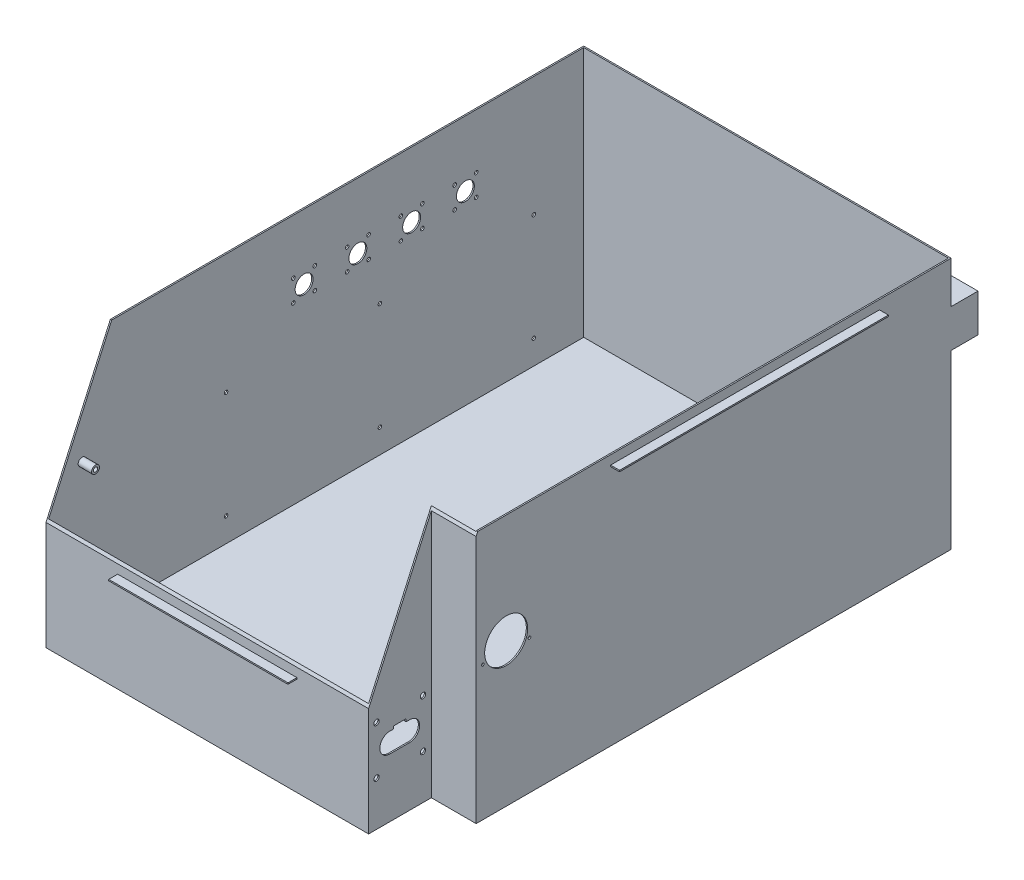
SolidWorks part; units mm, degrees
ref_plane "Front Plane" through (0, 0, 0) normal (0, 0, 1) x (1, 0, 0)
ref_plane "Top Plane" through (0, 0, 0) normal (0, 1, 0) x (1, 0, 0)
ref_plane "Right Plane" through (0, 0, 0) normal (1, 0, 0) x (0, 0, -1)
sketch "Sketch1" plane through (0, 0, 0) normal (0, 1, 0) x (1, 0, 0)
  line L1 (-205, 300) -> (205, 300)
  line L2 (-205, 300) -> (-205, -300)
  line L3 (-205, -300) -> (155, -300)
  line L4 (205, 300) -> (205, -230)
  line L6 (205, -230) -> (155, -230)
  line L7 (155, -230) -> (155, -300)
  line L8 (0, -330) -> (0, 330) construction
  point P1 (0, 300)
  point P12 (-205, -6.3782)
  dimension "D1" = 600
  dimension "D2" = 410
  dimension "D3" = 300
  dimension "D5" = 70
  dimension "D6" = 50
extrude "Boss-Extrude1" add sketch "Sketch1" along normal blind 1.5
sketch "Sketch2" plane through (0, 1.5, 0) normal (0, 1, 0) x (1, 0, 0)
  line L60 (-203.5, 298.5) -> (-203.5, -298.5)
  line L61 (-203.5, -298.5) -> (153.5, -298.5)
  line L62 (153.5, -298.5) -> (153.5, -228.5)
  line L63 (153.5, -228.5) -> (203.5, -228.5)
  line L64 (203.5, -228.5) -> (203.5, 298.5)
  line L65 (203.5, 298.5) -> (-203.5, 298.5)
  line L66 (-205, 300) -> (-205, -300)
  line L67 (-205, -300) -> (155, -300)
  line L68 (155, -300) -> (155, -230)
  line L69 (155, -230) -> (205, -230)
  line L70 (205, -230) -> (205, 300)
  line L71 (205, 300) -> (-205, 300)
  line L72 (-205, 300) -> (-205, -300)
  line L73 (-205, -300) -> (155, -300)
  line L74 (155, -300) -> (155, -230)
  line L75 (155, -230) -> (205, -230)
  line L76 (205, -230) -> (205, 300)
  line L77 (205, 300) -> (-205, 300)
  dimension "D1" = 0
  dimension "D2" = 1.5
extrude "Boss-Extrude2" add sketch "Sketch2" along normal blind 280
sketch "Sketch3" plane through (-205, 0, 0) normal (-1, 0, 0) x (0, 0, 1)
  line L3 (300, 281.5) -> (300, 0) construction
  line L4 (300, 121.1176) -> (228.1952, 281.5)
  line L6 (-300, 281.5) -> (300, 281.5) construction
  line L9 (300, 281.5) -> (300, 121.1176)
  line L10 (228.1952, 281.5) -> (300, 281.5)
sketch "Sketch4" plane through (0, 0, -300) normal (0, 0, -1) x (-1, 0, 0)
  line L0 (-205, 281.5) -> (-205, 0) construction
  line L1 (-205, 234.6761) -> (205, 234.6761)
  line L2 (-205, 234.6761) -> (-205, 192.2905)
  line L3 (-205, 192.2905) -> (205, 192.2905)
  line L4 (205, 234.6761) -> (205, 192.2905)
  line L5 (205, 281.5) -> (205, 0) construction
extrude "Boss-Extrude3" add sketch "Sketch4" along normal blind 30
extrude "Cut-Extrude1" cut sketch "Sketch3" against normal through all both and the other way through all
sketch "Sketch5" plane through (-205, 0, 0) normal (-1, 0, 0) x (0, 0, 1)
  line L0 (-178.5, 196.6666) -> (-178.5, 220.6666) construction
  line L5 (-178.5, 196.6666) -> (-154.5, 196.6666) construction
  line L6 (-178.5, 220.6666) -> (-154.5, 220.6666) construction
  line L7 (-154.5, 196.6666) -> (-154.5, 220.6666) construction
  line L8 (-178.5, 196.6666) -> (-154.5, 220.6666) construction
  line L9 (-178.5, 220.6666) -> (-154.5, 196.6666) construction
  line L10 (-118.5, 196.6666) -> (-118.5, 220.6666) construction
  line L11 (-118.5, 196.6666) -> (-94.5, 196.6666) construction
  line L14 (-118.5, 220.6666) -> (-94.5, 220.6666) construction
  line L16 (-94.5, 196.6666) -> (-94.5, 220.6666) construction
  line L17 (-118.5, 196.6666) -> (-94.5, 220.6666) construction
  line L20 (-118.5, 220.6666) -> (-94.5, 196.6666) construction
  line L22 (-58.5, 196.6666) -> (-58.5, 220.6666) construction
  line L23 (-58.5, 196.6666) -> (-34.5, 196.6666) construction
  line L26 (-58.5, 220.6666) -> (-34.5, 220.6666) construction
  line L28 (-298.5, 281.5) -> (-298.5, 1.5) construction
  line L29 (-34.5, 196.6666) -> (-34.5, 220.6666) construction
  line L30 (-58.5, 196.6666) -> (-34.5, 220.6666) construction
  line L31 (-58.5, 220.6666) -> (-34.5, 196.6666) construction
  line L32 (1.5, 196.6666) -> (1.5, 220.6666) construction
  line L33 (1.5, 196.6666) -> (25.5, 196.6666) construction
  line L34 (1.5, 220.6666) -> (25.5, 220.6666) construction
  line L35 (25.5, 196.6666) -> (25.5, 220.6666) construction
  line L36 (1.5, 196.6666) -> (25.5, 220.6666) construction
  line L37 (1.5, 220.6666) -> (25.5, 196.6666) construction
  circle A0 centre (-178.5, 220.6666) radius 2
  circle A2 centre (-154.5, 196.6666) radius 2
  circle A3 centre (-154.5, 220.6666) radius 2
  circle A4 centre (-166.5, 208.6666) radius 10
  circle A20 centre (-178.5, 196.6666) radius 2
  circle A21 centre (-118.5, 220.6666) radius 2
  circle A22 centre (-94.5, 196.6666) radius 2
  circle A23 centre (-94.5, 220.6666) radius 2
  circle A24 centre (-106.5, 208.6666) radius 10
  circle A25 centre (-118.5, 196.6666) radius 2
  circle A26 centre (-58.5, 220.6666) radius 2
  circle A27 centre (-34.5, 196.6666) radius 2
  circle A28 centre (-34.5, 220.6666) radius 2
  circle A29 centre (-46.5, 208.6666) radius 10
  circle A30 centre (-58.5, 196.6666) radius 2
  circle A31 centre (1.5, 220.6666) radius 2
  circle A32 centre (25.5, 196.6666) radius 2
  circle A33 centre (25.5, 220.6666) radius 2
  circle A34 centre (13.5, 208.6666) radius 10
  circle A35 centre (1.5, 196.6666) radius 2
  point P9 (-166.5, 208.6666)
  point P23 (-106.5, 208.6666)
  point P36 (-46.5, 208.6666)
  point P49 (13.5, 208.6666)
  dimension "D2" = 20
  dimension "D5" = 4
  dimension "D1" = 4
  dimension "D8" = 4
  dimension "D3" = 24
  dimension "D4" = 24
  dimension "D7" = 120
  dimension "D6" = 4
sketch "Sketch6" plane through (-203.5, 0, 0) normal (1, 0, 0) x (0, 0, -1)
  arc A0 (151.1392, 167.4539) -> (156.7272, 167.4539) centre (153.9332, 167.4539) ccw construction
  arc A1 (-68.8756, 167.4539) -> (-63.2876, 167.4539) centre (-66.0816, 167.4539) ccw construction
  arc A2 (-178.883, 167.4539) -> (-173.295, 167.4539) centre (-176.089, 167.4539) ccw construction
  arc A3 (151.1392, 167.4539) -> (156.7272, 167.4539) centre (153.9332, 167.4539) ccw
  arc A4 (-68.8756, 167.4539) -> (-63.2876, 167.4539) centre (-66.0816, 167.4539) ccw
  arc A5 (-178.883, 167.4539) -> (-173.295, 167.4539) centre (-176.089, 167.4539) ccw
  circle A6 centre (-176.089, 167.4539) radius 2.794
  circle A7 centre (-176.089, 167.4539) radius 4.5
  circle A8 centre (-64.4633, 167.4539) radius 4.5
  circle A9 centre (-64.4633, 167.4539) radius 2.794
  circle A10 centre (155.5515, 167.4539) radius 2.794
  circle A11 centre (155.5515, 167.4539) radius 4.5
  dimension "D1" = 9
extrude "Boss-Extrude4" [suppressed] add sketch "Sketch6" along normal blind 50 contours A4 A9 | A8 | A7 | A6 | A11 | A10
sketch "Sketch8" plane through (-203.5, 0, 0) normal (1, 0, 0) x (0, 0, -1)
  line L0 (298.5, 1.5) -> (-298.5, 1.5) construction
  line L1 (-298.5, 124.4679) -> (-298.5, 1.5) construction
  circle A0 centre (-261.2404, 161.0978) radius 2.39
  circle A1 centre (-261.2404, 161.0978) radius 4.39
  circle A2 centre (-203.5, 16.5) radius 2.39
  circle A3 centre (-203.5, 16.5) radius 4.39
  dimension "D3" = 4.78
  dimension "D4" = 2
  dimension "D1" = 155.7
  dimension "D2" = 15
  dimension "D5" = 95
extrude "Boss-Extrude5" add sketch "Sketch8" along normal blind 15
sketch "Sketch10" plane through (153.5, 0, 0) normal (-1, 0, 0) x (0, 0, 1)
  line L0 (254, 86.5) -> (259.25, 86.5) construction
  line L1 (254, 66.5) -> (276.5, 66.5) construction
  line L2 (276.5, 76.5) -> (254, 76.5) construction
  line L3 (298.5, 1.5) -> (228.5, 1.5) construction
  line L5 (259.25, 86.5) -> (259.25, 89.5) construction
  line L6 (259.25, 89.5) -> (271.25, 89.5) construction
  line L7 (271.25, 86.5) -> (271.25, 89.5) construction
  line L8 (298.5, 124.4679) -> (298.5, 1.5) construction
  line L9 (271.25, 86.5) -> (276.5, 86.5) construction
  line L10 (258.25, 90.5) -> (272.25, 90.5)
  line L11 (272.25, 87.5) -> (272.25, 90.5)
  line L12 (272.25, 87.5) -> (276.5, 87.5)
  line L13 (254, 65.5) -> (276.5, 65.5)
  line L14 (254, 87.5) -> (258.25, 87.5)
  line L15 (258.25, 87.5) -> (258.25, 90.5)
  line L17 (239.3, 49.55) -> (291.2, 49.55) construction
  line L18 (239.3, 49.55) -> (239.3, 103.45) construction
  line L19 (239.3, 103.45) -> (291.2, 103.45) construction
  line L20 (291.2, 49.55) -> (291.2, 103.45) construction
  line L21 (239.3, 49.55) -> (291.2, 103.45) construction
  line L22 (239.3, 103.45) -> (291.2, 49.55) construction
  arc A0 (254, 86.5) -> (254, 66.5) centre (254, 76.5) ccw construction
  arc A1 (276.5, 66.5) -> (276.5, 86.5) centre (276.5, 76.5) ccw construction
  arc A2 (276.5, 65.5) -> (276.5, 87.5) centre (276.5, 76.5) ccw
  arc A3 (254, 87.5) -> (254, 65.5) centre (254, 76.5) ccw
  circle A4 centre (239.3, 103.45) radius 3
  circle A5 centre (291.2, 103.45) radius 3
  circle A6 centre (239.3, 49.55) radius 3
  circle A7 centre (291.2, 49.55) radius 3
  point P12 (265.25, 89.5)
  point P13 (265.25, 76.5)
  point P26 (265.25, 76.5)
  dimension "D1" = 65
  dimension "D2" = 22.5
  dimension "D6" = 20
  dimension "D10" = 6
  dimension "D3" = 22
  dimension "D4" = 12
  dimension "D5" = 3
  dimension "D8" = 51.9
  dimension "D9" = 53.9
  dimension "D7" = 1
extrude "Cut-Extrude2" cut sketch "Sketch10" against normal up to surface (1.5 mm away)
sketch "Sketch11" plane through (153.5, 0, 0) normal (-1, 0, 0) x (0, 0, 1)
  line L0 (298.4737, 103.43) -> (298.4737, 49.53) construction
  line L13 (254, 66.5) -> (276.5, 66.5) construction
  line L14 (254, 86.5) -> (259.25, 86.5) construction
  line L15 (254, 66.5) -> (276.5, 66.5)
  line L19 (254, 86.5) -> (318.4237, 86.5)
  line L20 (272.25, 90.5) -> (258.25, 90.5)
  line L21 (272.25, 90.5) -> (258.25, 90.5)
  line L22 (272.25, 87.5) -> (272.25, 90.5)
  line L23 (272.25, 87.5) -> (272.25, 90.5)
  line L28 (330.4237, 86.5) -> (259.25, 86.5)
  line L29 (254.1078, 66) -> (276.5284, 66)
  line L30 (330.9237, 86) -> (258.6115, 86)
  line L31 (330.9237, 86) -> (330.9237, 91)
  line L32 (330.9237, 91) -> (317.9237, 91)
  line L33 (317.9237, 91) -> (317.9237, 87)
  line L34 (254.1078, 87) -> (317.9237, 87)
  line L36 (298.4737, 103.43) -> (350.3737, 103.43) construction
  line L43 (272.25, 90.5) -> (258.25, 90.5)
  line L44 (272.25, 90.5) -> (258.25, 90.5)
  line L45 (272.25, 87.5) -> (272.25, 90.5)
  line L46 (272.25, 87.5) -> (272.25, 90.5)
  line L47 (276.5, 87.5) -> (272.25, 87.5)
  line L48 (276.5, 87.5) -> (272.25, 87.5)
  line L49 (254, 65.5) -> (276.5, 65.5)
  line L50 (254, 65.5) -> (276.5, 65.5)
  line L51 (258.25, 87.5) -> (254, 87.5)
  line L52 (258.25, 87.5) -> (254, 87.5)
  line L53 (258.25, 90.5) -> (258.25, 87.5)
  line L54 (258.25, 90.5) -> (258.25, 87.5)
  line L55 (272.25, 90.5) -> (258.25, 90.5)
  line L56 (272.25, 90.5) -> (258.25, 90.5)
  line L57 (272.25, 87.5) -> (272.25, 90.5)
  line L58 (272.25, 87.5) -> (272.25, 90.5)
  line L59 (276.5, 87.5) -> (272.25, 87.5)
  line L60 (276.5, 87.5) -> (272.25, 87.5)
  line L61 (254, 65.5) -> (276.5, 65.5)
  line L62 (254, 65.5) -> (276.5, 65.5)
  line L63 (258.25, 87.5) -> (254, 87.5)
  line L64 (258.25, 87.5) -> (254, 87.5)
  line L65 (258.25, 90.5) -> (258.25, 87.5)
  line L66 (258.25, 90.5) -> (258.25, 87.5)
  line L67 (330.4237, 86.5) -> (330.4237, 90.5) construction
  line L68 (330.4237, 90.5) -> (318.4237, 90.5) construction
  line L69 (318.4237, 90.5) -> (318.4237, 86.5) construction
  line L70 (276.5, 87.5) -> (272.25, 87.5)
  line L71 (276.5, 87.5) -> (272.25, 87.5)
  line L72 (254, 65.5) -> (276.5, 65.5)
  line L73 (254, 65.5) -> (276.5, 65.5)
  line L74 (258.25, 87.5) -> (254, 87.5)
  line L75 (258.25, 87.5) -> (254, 87.5)
  line L76 (258.25, 90.5) -> (258.25, 87.5)
  line L77 (258.25, 90.5) -> (258.25, 87.5)
  arc A4 (276.5284, 66) -> (258.6115, 86) centre (274.6748, 82.3648) ccw
  arc A5 (276.5, 65.5) -> (276.5, 87.5) centre (276.5, 76.5) ccw
  arc A7 (276.5, 65.5) -> (276.5, 87.5) centre (276.5, 76.5) ccw
  arc A9 (254.1078, 87) -> (254.1078, 66) centre (249.4174, 76.5) ccw
  circle A10 centre (298.4737, 103.43) radius 3
  circle A11 centre (298.4737, 49.53) radius 3
  circle A12 centre (350.3737, 103.43) radius 3
  circle A13 centre (350.3737, 49.53) radius 3
  arc A16 (276.5, 66.5) -> (259.25, 86.5) centre (274.6748, 82.3648) ccw construction
  arc A17 (276.5, 65.5) -> (276.5, 87.5) centre (276.5, 76.5) ccw
  arc A18 (254, 87.5) -> (254, 65.5) centre (254, 76.5) ccw
  arc A19 (254, 87.5) -> (254, 65.5) centre (254, 76.5) ccw
  arc A20 (254, 86.5) -> (254, 66.5) centre (249.4174, 76.5) ccw construction
  arc A21 (276.5, 65.5) -> (276.5, 87.5) centre (276.5, 76.5) ccw
  arc A22 (254, 87.5) -> (254, 65.5) centre (254, 76.5) ccw
  arc A23 (254, 87.5) -> (254, 65.5) centre (254, 76.5) ccw
  arc A24 (276.5, 65.5) -> (276.5, 87.5) centre (276.5, 76.5) ccw
  arc A25 (276.5, 65.5) -> (276.5, 87.5) centre (276.5, 76.5) ccw
  arc A26 (254, 87.5) -> (254, 65.5) centre (254, 76.5) ccw
  arc A27 (254, 87.5) -> (254, 65.5) centre (254, 76.5) ccw
  dimension "D5" = 6
  dimension "D6" = 51.9
  dimension "D7" = 53.9
  dimension "D1" = 0
  dimension "D2" = 0
  dimension "D3" = 0
  dimension "D4" = 0.5
extrude "Cut-Extrude3" [suppressed] cut sketch "Sketch11" against normal through all
sketch "Sketch14" plane through (153.5, 0, 0) normal (-1, 0, 0) x (0, 0, 1)
  line L0 (300, 121.1176) -> (300, 0) construction
  line L1 (300, 0) -> (230, 0) construction
  circle A0 centre (235.1, 103.43) radius 3
  circle A1 centre (287, 103.43) radius 3
  circle A2 centre (287, 49.53) radius 3
  circle A3 centre (235.1, 49.53) radius 3
  dimension "D5" = 6
  dimension "D1" = 51.9
  dimension "D2" = 53.9
  dimension "D3" = 13
  dimension "D4" = 103.43
extrude "Cut-Extrude4" [suppressed] cut sketch "Sketch14" against normal up to surface (1.5 mm away)
sketch "Sketch15" plane through (203.5, 0, 0) normal (-1, 0, 0) x (0, 0, 1)
  line L1 (-213.5, 252.1363) -> (-198.5, 252.1363)
  line L2 (-213.5, 252.1363) -> (-213.5, 250.6363)
  line L3 (-213.5, 250.6363) -> (-198.5, 250.6363)
  line L4 (-198.5, 252.1363) -> (-198.5, 250.6363)
  line L5 (-298.5, 281.5) -> (-298.5, 1.5) construction
  line L6 (64.5, 252.1363) -> (84.5, 252.1363)
  line L7 (64.5, 250.6363) -> (84.5, 250.6363)
  line L8 (64.5, 252.1363) -> (64.5, 250.6363)
  line L9 (84.5, 252.1363) -> (84.5, 250.6363)
  dimension "D1" = 1.5
  dimension "D2" = 15
  dimension "D3" = 85
  dimension "D4" = 363
  dimension "D5" = 20
extrude "Boss-Extrude6" add sketch "Sketch15" along normal blind 13
ref_plane "Plane1" through (0, 0, -193.5) normal (0, 0, -1) x (-1, 0, 0)
sketch "Sketch17" plane through (0, 0, -198.5) normal (0, 0, 1) x (1, 0, 0)
  line L0 (203.5, 250.6363) -> (203.5, 235.6363)
  line L1 (203.5, 281.5) -> (203.5, 280.8193) construction
  line L2 (203.5, 235.6363) -> (190.5, 250.6363)
  line L3 (190.5, 250.6363) -> (203.5, 250.6363)
  dimension "D1" = 15
extrude "Boss-Extrude7" add sketch "Sketch17" against normal blind 1.5
ref_plane "Plane2" through (0, 0, 64.5) normal (0, 0, 1) x (1, 0, 0)
sketch "Sketch18" plane through (0, 0, 64.5) normal (0, 0, 1) x (1, 0, 0)
  line L0 (203.5, 250.6363) -> (203.5, 235.6363)
  line L1 (203.5, 281.5) -> (203.5, 280.8193) construction
  line L2 (203.5, 235.6363) -> (190.5, 250.6363)
  line L3 (190.5, 250.6363) -> (203.5, 250.6363)
  dimension "D1" = 15
extrude "Boss-Extrude8" add sketch "Sketch18" along normal blind 1.5
sketch "Sketch20" plane through (0, 252.1363, 0) normal (0, 1, 0) x (1, 0, 0)
  line L1 (190.5, 213.5) -> (203.5, 213.5) construction
  line L2 (190.5, 198.5) -> (190.5, 213.5) construction
  line L3 (190.5, -84.5) -> (203.5, -84.5) construction
  line L4 (190.5, -84.5) -> (190.5, -64.5) construction
  circle A0 centre (198, 206.5) radius 2.4159
  circle A1 centre (200.5, -77.5) radius 2
  dimension "D3" = 4
  dimension "D1" = 7
  dimension "D2" = 7.5
  dimension "D4" = 7
  dimension "D5" = 10
extrude "Cut-Extrude5" cut sketch "Sketch20" against normal up to surface (1.5 mm away) up to face at (197, 250.6363, -206.75)
extrude "Cut-Extrude7" cut sketch "Sketch5" against normal up to surface (1.5 mm away) up to face at (-203.5, 16.5, 199.11)
sketch "Sketch21" plane through (0, 0, -300) normal (0, 0, -1) x (-1, 0, 0)
  line L0 (-205, 281.5) -> (205, 281.5) construction
  line L1 (-150, 271.5) -> (150, 271.5)
  line L2 (-150, 271.5) -> (-150, 270)
  line L3 (-150, 270) -> (150, 270)
  line L4 (150, 271.5) -> (150, 270)
  point P6 (0, 281.5)
  point P7 (0, 271.5)
  dimension "D1" = 1.5
  dimension "D2" = 300
  dimension "D3" = 10
extrude "Boss-Extrude9" add sketch "Sketch21" along normal blind 10
sketch "Sketch22" plane through (-205, 0, 0) normal (-1, 0, 0) x (0, 0, 1)
  line L0 (-300, 281.5) -> (228.1952, 281.5) construction
  line L1 (-220, 271.5) -> (80, 271.5)
  line L2 (-220, 271.5) -> (-220, 270)
  line L3 (-220, 270) -> (80, 270)
  line L4 (80, 271.5) -> (80, 270)
  line L5 (-300, 281.5) -> (-300, 234.6761) construction
  dimension "D1" = 1.5
  dimension "D2" = 10
  dimension "D3" = 80
  dimension "D4" = 300
extrude "Boss-Extrude10" add sketch "Sketch22" along normal blind 10
ref_plane "Plane3" through (0, 0, -140) normal (0, 0, -1) x (-1, 0, 0)
sketch "Sketch23" plane through (0, 0, -140) normal (0, 0, -1) x (-1, 0, 0)
  line L0 (215, 270) -> (205, 270) construction
  line L1 (215, 270) -> (205, 270)
  line L2 (215, 270) -> (205, 260)
  line L3 (205, 281.5) -> (205, 234.6761) construction
  line L4 (205, 260) -> (205, 270)
  dimension "D1" = 10
extrude "Boss-Extrude11" add sketch "Sketch23" along normal mid plane 1.5
ref_plane "Plane4" through (0, 0, -10) normal (0, 0, 1) x (1, 0, 0)
sketch "Sketch24" plane through (0, 0, -10) normal (0, 0, 1) x (1, 0, 0)
  line L6 (-215, 270) -> (-205, 260)
  line L7 (-205, 260) -> (-205, 270)
  line L8 (-205, 270) -> (-215, 270)
  line L9 (-215, 270) -> (-205, 260)
  line L10 (-205, 260) -> (-205, 270)
  line L11 (-205, 270) -> (-215, 270)
  dimension "D1" = 0
extrude "Boss-Extrude12" add sketch "Sketch24" along normal mid plane 1.5
ref_plane "Plane5" through (100, 0, 0) normal (1, 0, 0) x (0, 0, -1)
sketch "Sketch25" plane through (100, 0, 0) normal (1, 0, 0) x (0, 0, -1)
  line L0 (310, 270) -> (300, 270)
  line L1 (300, 270) -> (300, 260)
  line L2 (300, 281.5) -> (300, 234.6761) construction
  line L3 (300, 260) -> (310, 270)
  dimension "D1" = 10
extrude "Boss-Extrude13" add sketch "Sketch25" along normal mid plane 1.5
ref_plane "Plane6" through (-100, 0, 0) normal (-1, 0, 0) x (0, 0, 1)
sketch "Sketch26" plane through (-100, 0, 0) normal (-1, 0, 0) x (0, 0, 1)
  line L3 (-310, 270) -> (-300, 260)
  line L4 (-300, 260) -> (-300, 270)
  line L5 (-300, 270) -> (-310, 270)
  line L6 (-310, 270) -> (-300, 260)
  line L7 (-300, 260) -> (-300, 270)
  line L8 (-300, 270) -> (-310, 270)
  dimension "D1" = 0
extrude "Boss-Extrude14" add sketch "Sketch26" along normal mid plane 1.5
mirror "Mirror1" about plane through (0, 0, 0) normal (1, 0, 0) of "Boss-Extrude11", "Boss-Extrude12", "Boss-Extrude10"
sketch "Sketch27" plane through (0, 0, 300) normal (0, 0, 1) x (1, 0, 0)
  line L0 (155, 121.1176) -> (-205, 121.1176) construction
  line L1 (-125, 111.1176) -> (75, 111.1176)
  line L2 (-125, 111.1176) -> (-125, 109.6176)
  line L3 (-125, 109.6176) -> (75, 109.6176)
  line L4 (75, 111.1176) -> (75, 109.6176)
  line L5 (155, 121.1176) -> (-205, 121.1176) construction
  point P6 (-25, 121.1176)
  point P7 (-25, 111.1176)
  dimension "D1" = 1.5
  dimension "D2" = 200
  dimension "D3" = 10
extrude "Boss-Extrude15" add sketch "Sketch27" along normal blind 10
ref_plane "Plane7" through (-95, 0, 0) normal (-1, 0, 0) x (0, 0, 1)
sketch "Sketch28" plane through (-95, 0, 0) normal (-1, 0, 0) x (0, 0, 1)
  line L0 (310, 109.6176) -> (300, 109.6176)
  line L1 (300, 109.6176) -> (300, 99.6176)
  line L2 (300, 121.1176) -> (300, 0) construction
  line L3 (300, 99.6176) -> (310, 109.6176)
  dimension "D1" = 10
extrude "Boss-Extrude16" add sketch "Sketch28" along normal mid plane 1.5
ref_plane "Plane8" through (45, 0, 0) normal (1, 0, 0) x (0, 0, -1)
sketch "Sketch29" plane through (45, 0, 0) normal (1, 0, 0) x (0, 0, -1)
  line L3 (-310, 109.6176) -> (-300, 99.6176)
  line L4 (-300, 99.6176) -> (-300, 109.6176)
  line L5 (-300, 109.6176) -> (-310, 109.6176)
  line L6 (-310, 109.6176) -> (-300, 99.6176)
  line L7 (-300, 99.6176) -> (-300, 109.6176)
  line L8 (-300, 109.6176) -> (-310, 109.6176)
  dimension "D1" = 0
extrude "Boss-Extrude17" add sketch "Sketch29" along normal mid plane 1.5
sketch "Sketch30" plane through (205, 0, 0) normal (1, 0, 0) x (0, 0, -1)
  line L1 (-230, 0) -> (300, 0) construction
  line L2 (-230, 277.4689) -> (-230, 0) construction
  circle A0 centre (-196.5, 160) radius 24
  circle A1 centre (-222.5, 150) radius 1.5
  circle A2 centre (-170.5, 150) radius 1.5
  dimension "D1" = 48
  dimension "D2" = 3
  dimension "D3" = 3
  dimension "D4" = 26
  dimension "D5" = 10
  dimension "D6" = 26
  dimension "D7" = 10
  dimension "D8" = 160
  dimension "D9" = 33.5
extrude "Cut-Extrude8" cut sketch "Sketch30" against normal up to surface (1.5 mm away) up to face at (203.5, 246.1363, -204)
sketch "Sketch31" plane through (0, 0, 0) normal (0, -1, 0) x (1, 0, 0)
  line L0 (205, -300) -> (-205, -300) construction
  line L1 (205, -276) -> (230, -276)
  line L2 (205, -276) -> (205, -300)
  line L3 (205, -300) -> (230, -300)
  line L4 (230, -276) -> (230, -300)
  line L64 (205, 228.1952) -> (205, -300) construction
  line L65 (205, -150.25) -> (230, -150.25)
  line L66 (205, -150.25) -> (205, -174.25)
  line L67 (205, -174.25) -> (230, -174.25)
  line L68 (230, -150.25) -> (230, -174.25)
  line L69 (205, -24.5) -> (230, -24.5)
  line L70 (205, -24.5) -> (205, -48.5)
  line L71 (205, -48.5) -> (230, -48.5)
  line L72 (230, -24.5) -> (230, -48.5)
  line L73 (205, 101.25) -> (230, 101.25)
  line L74 (205, 101.25) -> (205, 77.25)
  line L75 (205, 77.25) -> (230, 77.25)
  line L76 (230, 101.25) -> (230, 77.25)
  line L77 (205, 227) -> (230, 227)
  line L78 (205, 227) -> (205, 203)
  line L79 (205, 203) -> (230, 203)
  line L80 (230, 227) -> (230, 203)
  line L81 (-205, 139.4237) -> (-205, 163.4237)
  line L82 (-205, -237.8263) -> (-205, -213.8263)
  line L83 (-180, -112.0763) -> (-180, -88.0763)
  line L84 (-180, -213.8263) -> (-205, -213.8263)
  line L85 (-180, 265.1737) -> (-180, 289.1737)
  line L86 (-180, -112.0763) -> (-205, -112.0763)
  line L87 (-205, -112.0763) -> (-205, -88.0763) construction
  line L88 (-180, 13.6737) -> (-205, 13.6737)
  line L89 (-180, 139.4237) -> (-180, 163.4237)
  line L90 (-180, 37.6737) -> (-205, 37.6737)
  line L91 (-180, 265.1737) -> (-205, 265.1737)
  line L92 (-180, 163.4237) -> (-205, 163.4237)
  line L93 (-180, 13.6737) -> (-180, 37.6737)
  line L94 (-205, 13.6737) -> (-205, 37.6737)
  line L95 (-180, -237.8263) -> (-205, -237.8263)
  line L96 (-205, 265.1737) -> (-205, 289.1737) construction
  line L97 (-180, 289.1737) -> (-205, 289.1737)
  line L98 (-180, -88.0763) -> (-205, -88.0763)
  line L99 (-180, 139.4237) -> (-205, 139.4237)
  line L100 (-180, -237.8263) -> (-180, -213.8263)
  circle A0 centre (230, -288) radius 12
  circle A1 centre (230, -288) radius 4
  circle A30 centre (230, -162.25) radius 12
  circle A31 centre (230, -162.25) radius 4
  circle A32 centre (230, -36.5) radius 12
  circle A33 centre (230, -36.5) radius 4
  circle A34 centre (230, 89.25) radius 12
  circle A35 centre (230, 89.25) radius 4
  circle A36 centre (230, 215) radius 12
  circle A37 centre (230, 215) radius 4
  circle A38 centre (-205, 277.1737) radius 4
  circle A39 centre (-205, 151.4237) radius 12
  circle A40 centre (-205, -225.8263) radius 12
  circle A41 centre (-205, 25.6737) radius 4
  circle A42 centre (-205, 277.1737) radius 12
  circle A43 centre (-205, -100.0763) radius 4
  circle A44 centre (-205, -225.8263) radius 4
  circle A45 centre (-205, 25.6737) radius 12
  circle A46 centre (-205, -100.0763) radius 12
  circle A47 centre (-205, 151.4237) radius 4
  dimension "D3" = 8
  dimension "D8" = 8
  dimension "D1" = 24
  dimension "D2" = 25
  dimension "D5" = 101.75
  dimension "D4" = 5
  dimension "D6" = 24
  dimension "D7" = 25
  dimension "D9" = 101.75
extrude "Boss-Extrude18" [suppressed] add sketch "Sketch31" against normal blind 1.5 separate body
sketch "Sketch33" plane through (-205, 0, 0) normal (-1, 0, 0) x (0, 0, 1)
  line L0 (-300, 192.2905) -> (-300, 0) construction
  line L1 (-300, 0) -> (300, 0) construction
  circle A0 centre (-242.8, 147.77) radius 2
  circle A1 centre (-242.8, 28.39) radius 2
  circle A2 centre (-71.1, 147.77) radius 2
  circle A3 centre (-71.1, 28.39) radius 2
  circle A4 centre (100.6, 147.77) radius 2
  circle A5 centre (100.6, 28.39) radius 2
  dimension "D3" = 4
  dimension "D1" = 57.2
  dimension "D2" = 119.38
  dimension "D4" = 28.39
  dimension "D5" = 3
extrude "Cut-Extrude9" cut sketch "Sketch33" against normal up to surface (1.5 mm away) up to face at (-203.5, 196.6666, -36.5)
